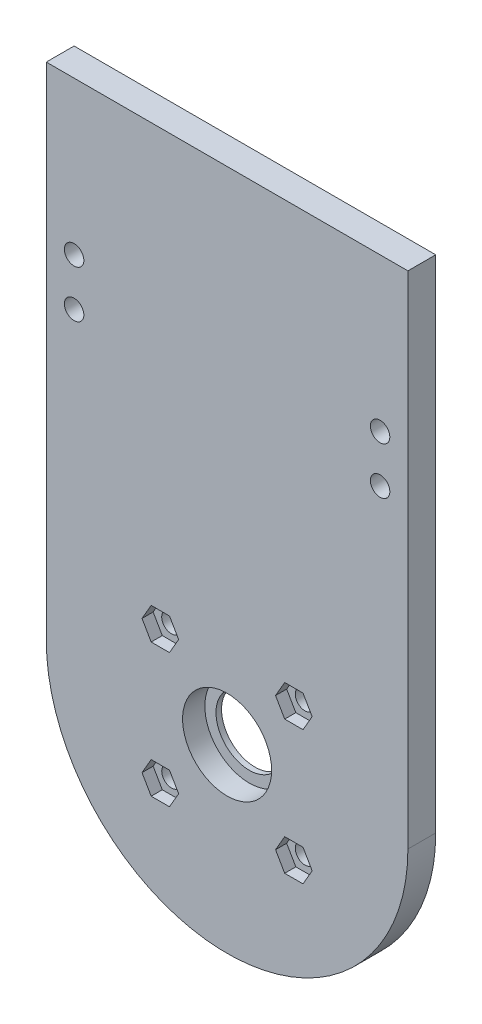
SolidWorks part; units mm, degrees
ref_plane "Front Plane" through (0, 0, 0) normal (0, 0, 1) x (1, 0, 0)
ref_plane "Top Plane" through (0, 0, 0) normal (0, 1, 0) x (1, 0, 0)
ref_plane "Right Plane" through (0, 0, 0) normal (1, 0, 0) x (0, 0, -1)
sketch "Sketch1" plane through (0, 0, 0) normal (0, 0, 1) x (1, 0, 0)
  line L2 (-32.5, 0) -> (-32.5, 90)
  line L3 (-32.5, 90) -> (32.5, 90)
  line L4 (32.5, 0) -> (32.5, 90)
  arc A0 (-32.5, 0) -> (32.5, 0) centre (0, 0) ccw
  dimension "D1" = 65
  dimension "D2" = 90
extrude "Boss-Extrude1" add sketch "Sketch1" along normal blind 5
sketch "Sketch2" plane through (0, 0, 5) normal (0, 0, 1) x (1, 0, 0)
  circle A0 centre (0, 0) radius 6
  dimension "D1" = 12
extrude "Cut-Extrude1" cut sketch "Sketch2" against normal through all
sketch "Sketch3" plane through (0, 0, 5) normal (0, 0, 1) x (1, 0, 0)
  circle A0 centre (0, 0) radius 8
  dimension "D1" = 16
extrude "Cut-Extrude2" cut sketch "Sketch3" against normal blind 4
sketch "Sketch4" plane through (0, 0, 5) normal (0, 0, 1) x (1, 0, 0)
  line L0 (-4.4468, 0) -> (0, 0) construction
  line L1 (0, 0) -> (0, 5.0638) construction
  circle A0 centre (-12, 12) radius 1.75
  circle A1 centre (12, 12) radius 1.75
  circle A2 centre (12, -12) radius 1.75
  circle A3 centre (-12, -12) radius 1.75
  dimension "D1" = 3.5
  dimension "D2" = 12
  dimension "D3" = 12
extrude "Cut-Extrude3" cut sketch "Sketch4" against normal through all
sketch "Sketch5" plane through (0, 0, 5) normal (0, 0, 1) x (1, 0, 0)
  line L0 (3.305, 0) -> (0, 0) construction
  line L1 (-8.7091, 12) -> (-10.3546, 14.85)
  line L2 (-10.3546, 14.85) -> (-13.6454, 14.85)
  line L3 (-13.6454, 14.85) -> (-15.2909, 12)
  line L4 (-15.2909, 12) -> (-13.6454, 9.15)
  line L5 (-13.6454, 9.15) -> (-10.3546, 9.15)
  line L6 (-10.3546, 9.15) -> (-8.7091, 12)
  line L7 (0, 0) -> (0, 2.8399) construction
  line L8 (10.3546, 9.15) -> (8.7091, 12)
  line L9 (13.6454, 9.15) -> (10.3546, 9.15)
  line L10 (15.2909, 12) -> (13.6454, 9.15)
  line L11 (13.6454, 14.85) -> (15.2909, 12)
  line L12 (10.3546, 14.85) -> (13.6454, 14.85)
  line L13 (8.7091, 12) -> (10.3546, 14.85)
  line L14 (8.7091, -12) -> (10.3546, -14.85)
  line L15 (10.3546, -14.85) -> (13.6454, -14.85)
  line L16 (13.6454, -14.85) -> (15.2909, -12)
  line L17 (15.2909, -12) -> (13.6454, -9.15)
  line L18 (13.6454, -9.15) -> (10.3546, -9.15)
  line L19 (10.3546, -9.15) -> (8.7091, -12)
  line L20 (-10.3546, -9.15) -> (-8.7091, -12)
  line L21 (-13.6454, -9.15) -> (-10.3546, -9.15)
  line L22 (-15.2909, -12) -> (-13.6454, -9.15)
  line L23 (-13.6454, -14.85) -> (-15.2909, -12)
  line L24 (-10.3546, -14.85) -> (-13.6454, -14.85)
  line L25 (-8.7091, -12) -> (-10.3546, -14.85)
  circle A0 centre (-12, 12) radius 2.85 construction
  circle A1 centre (12, 12) radius 2.85 construction
  circle A2 centre (12, -12) radius 2.85 construction
  circle A3 centre (-12, -12) radius 2.85 construction
  dimension "D1" = 5.7
extrude "Cut-Extrude4" cut sketch "Sketch5" against normal blind 2
sketch "Sketch6" plane through (0, 0, 5) normal (0, 0, 1) x (1, 0, 0)
  line L0 (32.5, 90) -> (-32.5, 90) construction
  line L1 (-32.5, 90) -> (-32.5, 0) construction
  line L2 (0, 43.8862) -> (0, 50.1713) construction
  circle A0 centre (-27.5, 62.5) radius 1.75
  circle A1 centre (-27.5, 54) radius 1.75
  circle A2 centre (27.5, 54) radius 1.75
  circle A3 centre (27.5, 62.5) radius 1.75
  dimension "D3" = 3.5
  dimension "D5" = 3.5
  dimension "D1" = 27.5
  dimension "D2" = 5
  dimension "D4" = 8.5
  dimension "D6" = 5
extrude "Cut-Extrude5" cut sketch "Sketch6" against normal through all
